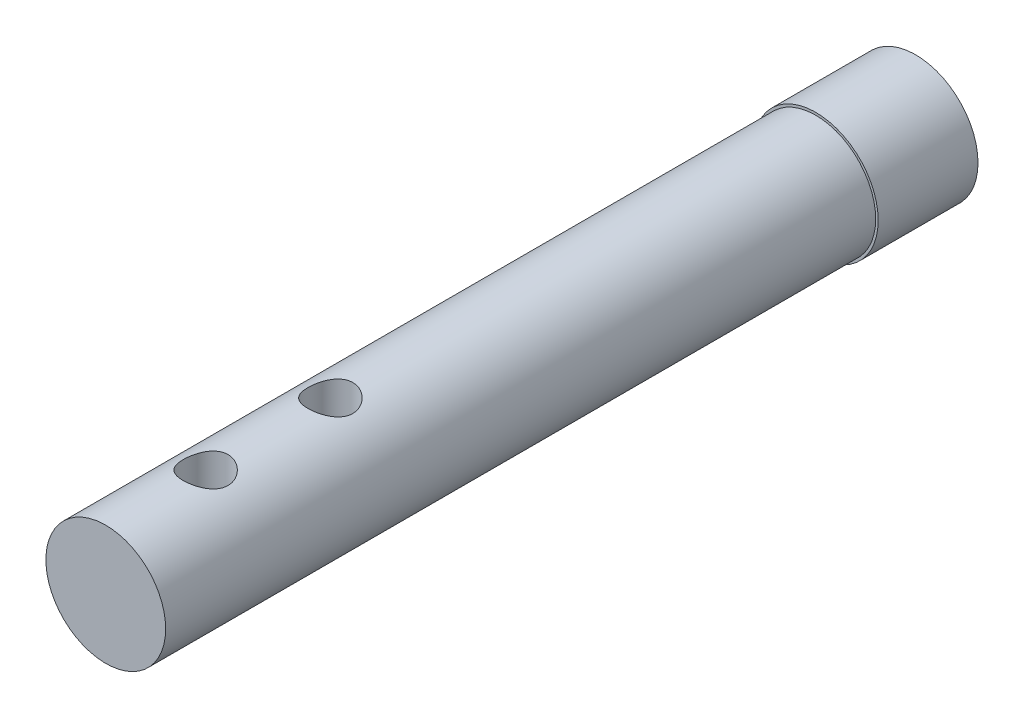
SolidWorks part; units mm, degrees
material "ASTM A36 Steel"
ref_plane "Front Plane" through (0, 0, 0) normal (0, 0, 1) x (1, 0, 0)
ref_plane "Top Plane" through (0, 0, 0) normal (0, 1, 0) x (1, 0, 0)
ref_plane "Right Plane" through (0, 0, 0) normal (1, 0, 0) x (0, 0, -1)
sketch "Sketch1" plane through (0, 0, 0) normal (0, 0, 1) x (1, 0, 0)
  circle A0 centre (0, 0) radius 10
  dimension "D1" = 20
extrude "Boss-Extrude1" add sketch "Sketch1" along normal blind 15
sketch "Sketch2" plane through (0, 0, 15) normal (0, 0, 1) x (1, 0, 0)
  circle A0 centre (0, 0) radius 12.5
  dimension "D1" = 25
extrude "Boss-Extrude2" add sketch "Sketch2" along normal blind 20
sketch "Sketch3" plane through (0, 0, 35) normal (0, 0, 1) x (1, 0, 0)
  circle A0 centre (0, 0) radius 12
  dimension "D1" = 24
extrude "Boss-Extrude3" add sketch "Sketch3" along normal blind 142.26
sketch "Sketch4" plane through (0, 0, 0) normal (0, 1, 0) x (1, 0, 0)
  line L0 (-12, -177.26) -> (12, -177.26) construction
  circle A0 centre (0, -157.26) radius 4.5
  dimension "D1" = 9
  dimension "D2" = 20
extrude "Cut-Extrude1" cut sketch "Sketch4" against normal through all both and the other way through all
sketch "Sketch5" plane through (0, 0, 0) normal (0, 1, 0) x (1, 0, 0)
  line L1 (12.5, -15) -> (-37.6297, -15)
  line L2 (12.5, -15) -> (12.5, 4.8742)
  line L3 (12.5, 4.8742) -> (-37.6297, 4.8742)
  line L4 (-37.6297, -15) -> (-37.6297, 4.8742)
extrude "Cut-Extrude2" cut sketch "Sketch5" against normal through all both and the other way through all
pattern_linear "LPattern1" count 2 spacing 25 along (0, 0, -1) of "Cut-Extrude1"
